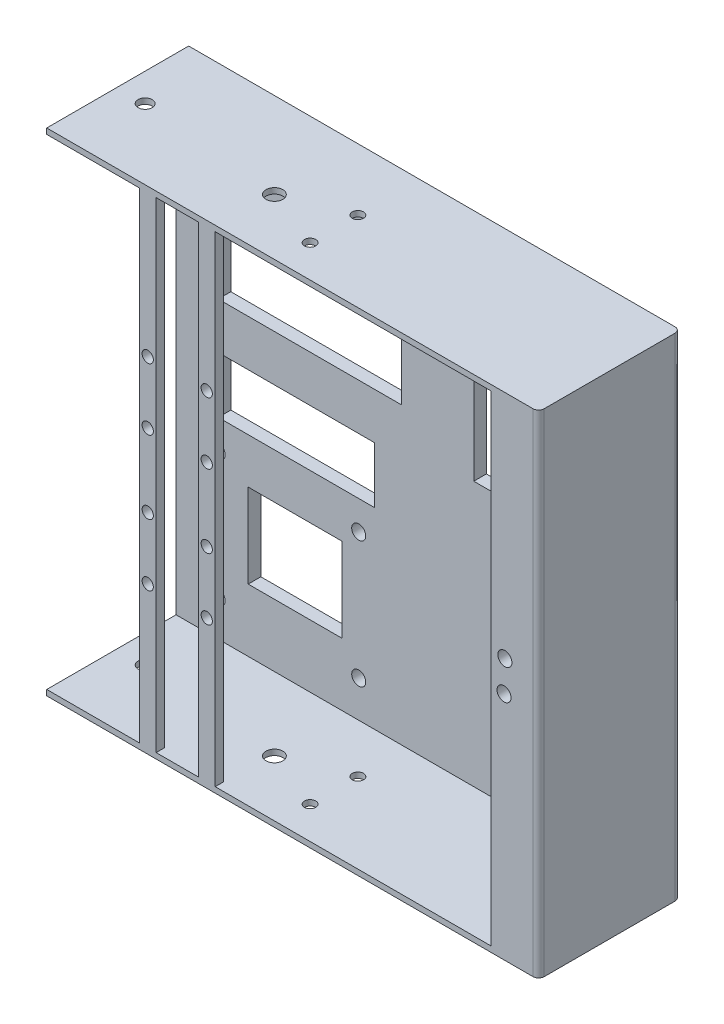
SolidWorks part; units mm, degrees
ref_plane "Plan de face" through (0, 0, 0) normal (0, 0, 1) x (1, 0, 0)
ref_plane "Plan de dessus" through (0, 0, 0) normal (0, 1, 0) x (1, 0, 0)
ref_plane "Plan de droite" through (0, 0, 0) normal (1, 0, 0) x (0, 0, -1)
other "Carte arduino"
sketch "Esquisse1" plane through (0, 0, 0) normal (0, 0, 1) x (1, 0, 0)
  line L1 (0, 0) -> (175, 0)
  line L2 (0, 0) -> (0, 175)
  line L3 (0, 175) -> (175, 175)
  line L4 (175, 0) -> (175, 175)
  dimension "D1" = 175
  dimension "D2" = 175
extrude "Boss.-Extru.1" add sketch "Esquisse1" along normal blind 4.5001
sketch "Esquisse9" plane through (0, 0, 4.5001) normal (0, 0, 1) x (1, 0, 0)
  line L0 (175, 0) -> (175, 175) construction
  line L1 (0, 0) -> (175, 0)
  line L2 (0, 0) -> (0, 2)
  line L4 (175, 0) -> (175, 4)
  line L5 (175, 175) -> (0, 175) construction
  line L6 (175, 0) -> (172, 0)
  line L7 (175, 0) -> (175, 175)
  line L8 (175, 175) -> (173, 175)
  line L10 (0, 2) -> (173, 2)
  line L11 (0, 175) -> (175, 175)
  line L12 (0, 175) -> (0, 173)
  line L14 (175, 175) -> (175, 146)
  line L15 (173, 2) -> (173, 173)
  line L16 (173, 173) -> (0, 173)
  line M4 (0, 175) -> (0, 0)
  line M5 (0, 0) -> (175, 0)
  line M6 (175, 0) -> (175, 175)
  line M7 (175, 175) -> (0, 175)
  dimension "D1" = 2
  dimension "D2" = 2
  dimension "D3" = 2
extrude "Boss.-Extru.4" add sketch "Esquisse9" along normal blind 46 contours L16 L15 L10 L1 L7 M4 M5 M6 M7
sketch "Esquisse12" plane through (173, 0, 0) normal (-1, 0, 0) x (0, 0, 1)
  line L0 (50.5001, 173) -> (4.5001, 173) construction
  line L1 (50.5001, 2) -> (46.5001, 2)
  line L2 (50.5001, 2) -> (50.5001, 173)
  line L3 (50.5001, 173) -> (46.5001, 173)
  line L4 (46.5001, 2) -> (46.5001, 173)
  dimension "D1" = 4
extrude "Boss.-Extru.5" add sketch "Esquisse12" along normal blind 15
sketch "Esquisse13" plane through (0, 0, 50.5001) normal (0, 0, 1) x (1, 0, 0)
  line L8 (158, 2) -> (158, 173) construction
  line L9 (175, 175) -> (0, 175) construction
  circle A0 centre (162.6954, 82.0042) radius 2.5
  circle A1 centre (163, 93) radius 2.5
  dimension "D1" = 82
  dimension "D2" = 11
  dimension "D4" = 5
extrude "Enlèv. mat.-Extru.1" cut sketch "Esquisse13" against normal blind 15
sketch "Esquisse15" plane through (0, 0, 0) normal (0, -1, 0) x (1, 0, 0)
  line L0 (0, 50.5001) -> (175, 50.5001) construction
  line L3 (0, 50.5001) -> (0, 0) construction
  circle A0 centre (10, 25.5001) radius 2.5
  dimension "D1" = 5
  dimension "D2" = 25
  dimension "D3" = 10
extrude "Enlèv. mat.-Extru.2" cut sketch "Esquisse15" against normal through all
sketch "Esquisse18" plane through (0, 0, 0) normal (0, 0, -1) x (-1, 0, 0)
  line L0 (0, 0) -> (-175, 0) construction
  line L1 (-155, 165) -> (-165, 165)
  line L2 (-155, 165) -> (-155, 10)
  line L3 (-155, 10) -> (-165, 10)
  line L4 (-165, 165) -> (-165, 10)
  line L5 (-175, 0) -> (-175, 175) construction
  dimension "D1" = 155
  dimension "D2" = 10
  dimension "D3" = 10
  dimension "D4" = 10
extrude "Enlèv. mat.-Extru.3" cut sketch "Esquisse18" against normal blind 15
sketch "Esquisse19" plane through (0, 0, 0) normal (0, 0, -1) x (-1, 0, 0)
  line L0 (-10, 150) -> (-10, 101.66) construction
  line L5 (-92.63, 150) -> (-10, 150) construction
  line L6 (-175, 175) -> (0, 175) construction
  line L8 (0, 175) -> (0, 0) construction
  circle A0 centre (-92.63, 150) radius 1.625
  circle A1 centre (-10, 150) radius 1.625
  circle A2 centre (-10, 101.66) radius 1.625
  dimension "D1" = 3.25
  dimension "D2" = 3.25
  dimension "D3" = 3.25
  dimension "D4" = 82.63
  dimension "D5" = 48.34
  dimension "D6" = 25
  dimension "D7" = 10
extrude "Enlèv. mat.-Extru.4" cut sketch "Esquisse19" against normal blind 15
fillet "Congé4" radius 2 1 edges at (173, 87.5, 46.5001)
fillet "Congé5" radius 2 1 edges at (175, 87.5, 50.5001)
fillet "Congé6" radius 2 1 edges at (175, 87.5, 0)
sketch "Esquisse22" plane through (0, 0, 0) normal (0, 0, -1) x (-1, 0, 0)
  line L0 (0, 175) -> (0, 0) construction
  line L1 (-10, 10) -> (-70, 10) construction
  line L2 (-10, 10) -> (-10, 65) construction
  line L3 (-10, 65) -> (-70, 65) construction
  line L4 (-70, 10) -> (-70, 65) construction
  line L5 (0, 0) -> (-173, 0) construction
  line L7 (-15, 15) -> (-65, 15) construction
  line L8 (-15, 15) -> (-15, 60) construction
  line L9 (-15, 60) -> (-65, 60) construction
  line L10 (-65, 15) -> (-65, 60) construction
  circle A0 centre (-15, 15) radius 2.5
  circle A1 centre (-65, 15) radius 2.5
  circle A2 centre (-65, 60) radius 2.5
  circle A3 centre (-15, 60) radius 2.5
  dimension "D9" = 5
  dimension "D10" = 5
  dimension "D11" = 5
  dimension "D12" = 5
  dimension "D1" = 55
  dimension "D2" = 60
  dimension "D3" = 10
  dimension "D4" = 10
  dimension "D5" = 5
  dimension "D6" = 5
  dimension "D7" = 5
  dimension "D8" = 5
extrude "Enlèv. mat.-Extru.5" cut sketch "Esquisse22" against normal blind 10
sketch "Esquisse27" plane through (0, 0, 0) normal (0, 0, -1) x (-1, 0, 0)
  line L0 (-155, 10) -> (-155, 165) construction
  line L1 (-105.9221, 165) -> (-155, 165)
  line L2 (-105.9221, 165) -> (-105.9221, 96.1142)
  line L3 (-105.9221, 96.1142) -> (-155, 96.1142)
  line L4 (-155, 165) -> (-155, 96.1142)
  line L5 (0, 175) -> (0, 0) construction
  line L6 (-15, 106.7907) -> (-80.157, 106.7907)
  line L7 (-15, 106.7907) -> (-15, 144.3052)
  line L8 (-15, 144.3052) -> (-80.157, 144.3052)
  line L9 (-80.157, 106.7907) -> (-80.157, 144.3052)
  line L10 (-25.6716, 24.2905) -> (-59.0142, 24.2905)
  line L11 (-25.6716, 24.2905) -> (-25.6716, 54.1888)
  line L12 (-25.6716, 54.1888) -> (-59.0142, 54.1888)
  line L13 (-59.0142, 24.2905) -> (-59.0142, 54.1888)
  line L14 (-15, 169.3543) -> (-85, 169.3543)
  line L15 (-15, 169.3543) -> (-15, 159.3543)
  line L16 (-15, 159.3543) -> (-85, 159.3543)
  line L17 (-85, 169.3543) -> (-85, 159.3543)
  line L18 (-15, 70.3283) -> (-70.6658, 70.3283)
  line L19 (-15, 70.3283) -> (-15, 90.3283)
  line L20 (-15, 90.3283) -> (-70.6658, 90.3283)
  line L21 (-70.6658, 70.3283) -> (-70.6658, 90.3283)
  line L22 (-155, 165) -> (-165, 165) construction
  dimension "D1" = 20
  dimension "D2" = 10
  dimension "D3" = 70
  dimension "D4" = 15
  dimension "D5" = 15
  dimension "D6" = 15
  dimension "D7" = 0
extrude "Enlèv. mat.-Extru.8" cut sketch "Esquisse27" against normal blind 7.5
sketch "Esquisse28" plane through (0, 2, 0) normal (0, 1, 0) x (1, 0, 0)
  line L0 (0, -50.5001) -> (158, -50.5001) construction
  line L1 (38.9277, -50.5001) -> (32.9277, -50.5001)
  line L2 (38.9277, -50.5001) -> (38.9277, -47.5001)
  line L3 (38.9277, -47.5001) -> (32.9277, -47.5001)
  line L4 (32.9277, -50.5001) -> (32.9277, -47.5001)
  line L6 (53.9277, -50.5001) -> (59.9277, -50.5001)
  line L7 (53.9277, -50.5001) -> (53.9277, -47.5001)
  line L8 (53.9277, -47.5001) -> (59.9277, -47.5001)
  line L9 (59.9277, -50.5001) -> (59.9277, -47.5001)
  dimension "D1" = 6
  dimension "D2" = 3
  dimension "D3" = 3
  dimension "D4" = 6
  dimension "D5" = 15
extrude "Boss.-Extru.8" add sketch "Esquisse28" along normal up to next
sketch "Esquisse29" plane through (0, 0, 50.5001) normal (0, 0, 1) x (1, 0, 0)
  line L0 (173, 0) -> (173, 175) construction
  line L1 (173, 77.5) -> (0, 77.5) construction
  line L2 (173, 77.5) -> (173, 97.5) construction
  line L3 (173, 97.5) -> (0, 97.5) construction
  line L4 (0, 77.5) -> (0, 97.5) construction
  line L5 (0, 0) -> (173, 0) construction
  line L6 (59.9277, 97.5) -> (53.9277, 77.5) construction
  line L7 (59.9277, 173) -> (59.9277, 2) construction
  line L8 (53.9277, 173) -> (53.9277, 2) construction
  line L9 (38.9633, 97.5) -> (32.9277, 77.5) construction
  line L10 (32.9277, 173) -> (32.9277, 2) construction
  line L11 (56.9277, 74.5) -> (56.9277, 52.5) construction
  line L12 (35.9277, 74.5) -> (35.9277, 52.5) construction
  line L13 (56.9277, 74.5) -> (9.4496, 74.5) construction
  line L14 (56.9277, 122.5) -> (56.9277, 100.5) construction
  line L15 (56.9277, 100.5) -> (35.9277, 100.5) construction
  line L16 (35.9277, 100.5) -> (35.9277, 122.5) construction
  circle A0 centre (56.9277, 74.5) radius 2
  circle A1 centre (35.9277, 74.5) radius 2
  circle A2 centre (56.9277, 52.5) radius 2
  circle A3 centre (35.9277, 52.5) radius 2
  circle A4 centre (56.9277, 100.5) radius 2
  circle A5 centre (35.9277, 100.5) radius 2
  circle A6 centre (35.9277, 122.5) radius 2
  circle A7 centre (56.9277, 122.5) radius 2
  dimension "D3" = 4
  dimension "D4" = 4
  dimension "D5" = 3
  dimension "D6" = 4
  dimension "D7" = 4
  dimension "D8" = 22
  dimension "D12" = 4
  dimension "D13" = 4
  dimension "D14" = 4
  dimension "D15" = 4
  dimension "D1" = 20
  dimension "D2" = 77.5
  dimension "D9" = 22
  dimension "D10" = 3
  dimension "D11" = 3
  dimension "D16" = 22
  dimension "D17" = 22
extrude "Enlèv. mat.-Extru.9" cut sketch "Esquisse29" against normal up to vertex (3 mm away)
sketch "Esquisse30" plane through (0, 2, 0) normal (0, 1, 0) x (1, 0, 0)
  line L0 (56, -19.5001) -> (119, -19.5001) construction
  line L1 (119, -19.5001) -> (119, -41.5001) construction
  line L2 (119, -41.5001) -> (56, -41.5001) construction
  line L3 (56, -41.5001) -> (56, -19.5001) construction
  line L4 (82.2, -41.5001) -> (82.2, -19.5001) construction
  line L5 (0, -50.5001) -> (0, -4.5001) construction
  line L6 (0, -50.5001) -> (173, -50.5001) construction
  circle A0 centre (61, -30.5001) radius 3
  circle A1 centre (82.2, -39.0001) radius 2
  circle A2 centre (82.2, -22.0001) radius 2
  point P12 (42.0993, -13.653)
  point P13 (0, 0)
  dimension "D1" = 6
  dimension "D5" = 4
  dimension "D6" = 4
  dimension "D8" = 2.5
  dimension "D9" = 21.2
  dimension "D2" = 63
  dimension "D3" = 22
  dimension "D4" = 11
  dimension "D7" = 17
  dimension "D10" = 5
  dimension "D11" = 56
  dimension "D12" = 20
extrude "Enlèv. mat.-Extru.10" cut sketch "Esquisse30" along normal blind 199 and the other way blind 10
sketch "Esquisse31" plane through (0, 0, 50.5001) normal (0, 0, 1) x (1, 0, 0)
  line L0 (168.6799, 77.5) -> (168.6799, 97.5) construction
  line L1 (158, 2) -> (158, 173) construction
  line L2 (0, 0) -> (173, 0) construction
  line L4 (171.5445, 77.5) -> (151.5445, 77.5) construction
  line L5 (151.5445, 77.5) -> (151.5445, 60.5) construction
  line L6 (151.5445, 60.5) -> (171.5445, 60.5) construction
  line L7 (171.5445, 60.5) -> (171.5445, 77.5) construction
  circle A0 centre (169, 62.75) radius 1.25
  circle A1 centre (169, 75.25) radius 1.25
  dimension "D5" = 2.5
  dimension "D6" = 2.5
  dimension "D1" = 77.5
  dimension "D2" = 17
  dimension "D3" = 20
  dimension "D4" = 12.5
  dimension "D7" = 2.25
  dimension "D8" = 11
  dimension "D9" = 11
